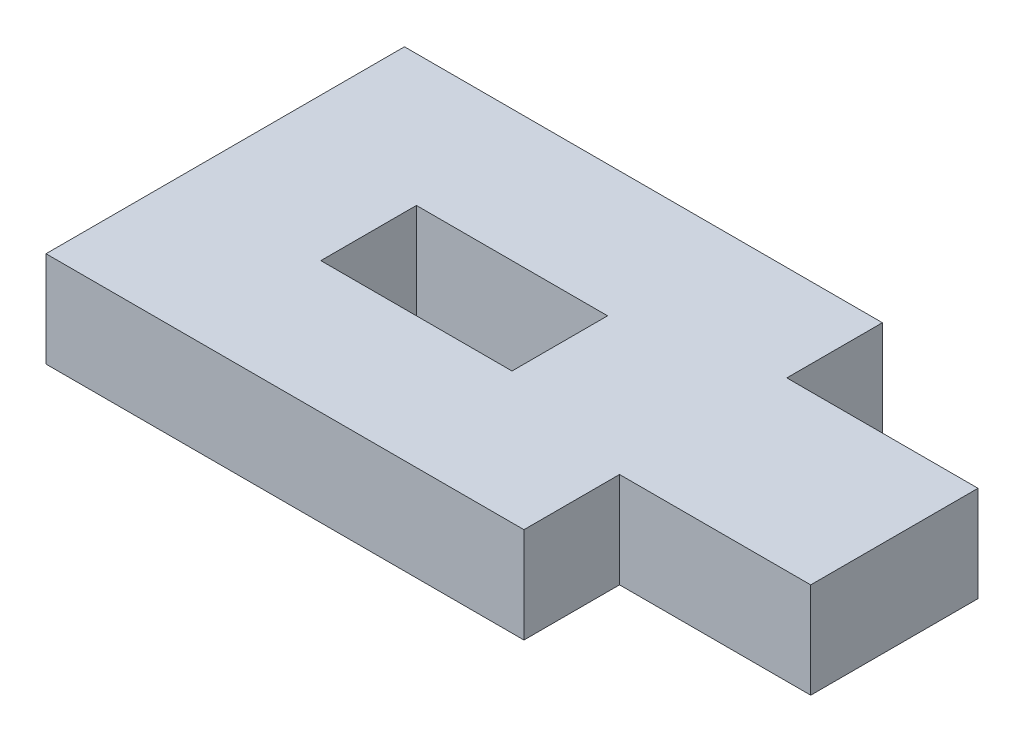
SolidWorks part; units mm, degrees
ref_plane "Front Plane" through (0, 0, 0) normal (0, 0, 1) x (1, 0, 0)
ref_plane "Top Plane" through (0, 0, 0) normal (0, 1, 0) x (1, 0, 0)
ref_plane "Right Plane" through (0, 0, 0) normal (1, 0, 0) x (0, 0, -1)
sketch "Sketch1" plane through (0, 0, 0) normal (0, 1, 0) x (1, 0, 0)
  line L1 (-10, 7.5) -> (10, 7.5)
  line L2 (-10, 7.5) -> (-10, -7.5)
  line L3 (-10, -7.5) -> (10, -7.5)
  line L4 (10, 7.5) -> (10, -7.5)
  line L6 (4, -2) -> (-4, -2)
  line L7 (4, -2) -> (4, 2)
  line L8 (4, 2) -> (-4, 2)
  line L9 (-4, -2) -> (-4, 2)
  point P4 (0, 2)
  point P10 (0, 7.5)
  point P11 (-4, 0)
  point P12 (-10, 0)
  dimension "D1" = 8
  dimension "D2" = 4
  dimension "D3" = 20
  dimension "D4" = 15
extrude "Boss-Extrude1" add sketch "Sketch1" along normal blind 4
sketch "Sketch2" plane through (0, 0, 0) normal (0, 1, 0) x (1, 0, 0)
  line L0 (10, 3.5) -> (18, 3.5)
  line L1 (10, -7.5) -> (10, 7.5) construction
  line L2 (18, 3.5) -> (18, -3.5)
  line L3 (18, -3.5) -> (10, -3.5)
  line L4 (10, 3.5) -> (10, -3.5)
  point P6 (10, 0)
  point P7 (18, 0)
  dimension "D1" = 7
  dimension "D2" = 8
extrude "Boss-Extrude3" add sketch "Sketch2" along normal blind 4
